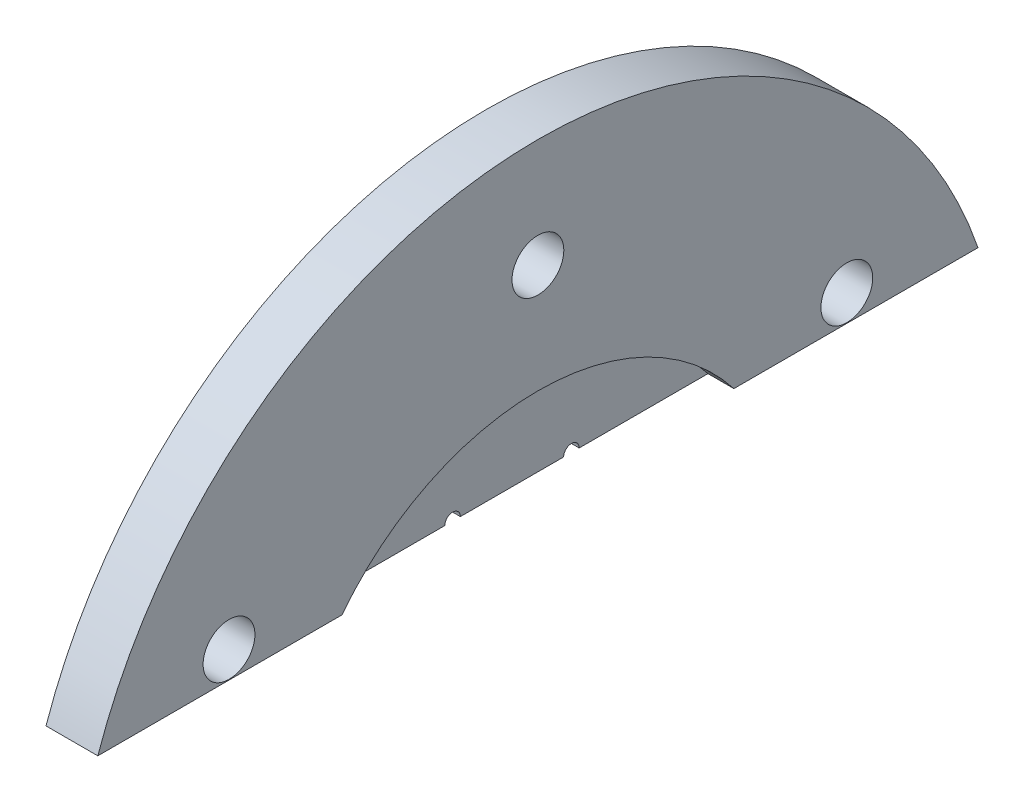
SolidWorks part; units mm, degrees
ref_plane "Front Plane" through (0, 0, 0) normal (0, 0, 1) x (1, 0, 0)
ref_plane "Top Plane" through (0, 0, 0) normal (0, 1, 0) x (1, 0, 0)
ref_plane "Right Plane" through (0, 0, 0) normal (1, 0, 0) x (0, 0, -1)
sketch "Sketch1" plane through (0, 0, 0) normal (1, 0, 0) x (0, 0, -1)
  circle A0 centre (0, 0) radius 89.825
  circle A1 centre (0, 0) radius 47.825
  dimension "D1" = 179.65
  dimension "D2" = 95.65
extrude "Boss-Extrude1" add sketch "Sketch1" along normal blind 10
sketch "Sketch3" plane through (0, 0, 0) normal (-1, 0, 0) x (0, 0, 1)
  circle A0 centre (0, 0) radius 47.825
  dimension "D1" = 95.65
extrude "tbh idk" add sketch "Sketch3" against normal blind 5
sketch "Sketch4" plane through (0, 0, 0) normal (-1, 0, 0) x (0, 0, 1)
  circle A0 centre (0, 0) radius 47.825
  dimension "D1" = 95.65
extrude "Extrusion to Fuel Man" add sketch "Sketch4" along normal blind 5
sketch "Ox Profile" plane through (-5, 0, 0) normal (-1, 0, 0) x (0, 0, 1)
  line L0 (0, 23.8051) -> (0, 34.7601) construction
  line L1 (0, -8.25) -> (0, 8.25) construction
  circle A0 centre (0, 29.2826) radius 1.25 construction
  circle A1 centre (11.4641, 29.2826) radius 1.5
  circle A2 centre (-11.4641, 29.2826) radius 1.5
  point P11 (0, 29.2826)
  dimension "D1" = 2.5
  dimension "D3" = 3
  dimension "D2" = 29.2826
  dimension "D4" = 11.4641
extrude "Ox Downcomer" cut sketch "Ox Profile" against normal up to next
pattern_circular "Ox Orifices" count 3 over 360 about axis through (0, -0.0577, 0) along (1, 0, 0) of "Ox Downcomer"
sketch "Sketch7" plane through (-5, 0, 0) normal (-1, 0, 0) x (0, 0, 1)
  line L0 (-6.9641, 29.2826) -> (6.9641, 29.2826) construction
  line L1 (-31.0915, -4.7131) -> (-11.4641, 29.2826) construction
  line L2 (-34.9886, -2.4631) -> (-15.3612, 31.5326)
  line L3 (31.0915, -4.7131) -> (11.4641, 29.2826) construction
  line L4 (15.3612, 31.5326) -> (34.9886, -2.4631)
  line L5 (-19.6274, -24.5695) -> (19.6274, -24.5695) construction
  line L6 (-19.6274, -29.0695) -> (19.6274, -29.0695)
  circle A0 centre (-11.4641, 29.2826) radius 4.5 construction
  circle A1 centre (11.4641, 29.2826) radius 4.5 construction
  arc A2 (-6.9641, 29.2826) -> (6.9641, 29.2826) centre (0, 29.2826) ccw
  circle A3 centre (31.0915, -4.7131) radius 4.5 construction
  arc A4 (28.8415, -8.6102) -> (21.8774, -20.6724) centre (25.3595, -14.6413) ccw
  circle A5 centre (19.6274, -24.5695) radius 4.5 construction
  circle A6 centre (-19.6274, -24.5695) radius 4.5 construction
  arc A7 (-21.8774, -20.6724) -> (-28.8415, -8.6102) centre (-25.3595, -14.6413) ccw
  circle A8 centre (-31.0915, -4.7131) radius 4.5 construction
  arc A9 (-15.3612, 31.5326) -> (-6.9641, 29.2826) centre (-11.4641, 29.2826) cw
  arc A10 (-34.9886, -2.4631) -> (-28.8415, -8.6102) centre (-31.0915, -4.7131) ccw
  arc A11 (6.9641, 29.2826) -> (15.3612, 31.5326) centre (11.4641, 29.2826) cw
  arc A12 (28.8415, -8.6102) -> (34.9886, -2.4631) centre (31.0915, -4.7131) ccw
  arc A13 (21.8774, -20.6724) -> (19.6274, -29.0695) centre (19.6274, -24.5695) cw
  arc A14 (-21.8774, -20.6724) -> (-19.6274, -29.0695) centre (-19.6274, -24.5695) ccw
  circle A15 centre (0, 0) radius 47.825
  point P25 (0, 0)
  dimension "D2" = 4.5
  dimension "D3" = 95.65
  dimension "D1" = 3
extrude "Fuel Blockers" cut sketch "Sketch7" against normal blind 5
sketch "Sketch8" plane through (5, 0, 0) normal (1, 0, 0) x (0, 0, -1)
  circle A0 centre (0, 0) radius 25.085
  dimension "D1" = 50.17
extrude "TI Cut Extrude" cut sketch "Sketch8" against normal through all
sketch "Sketch9" plane through (0, 0, 0) normal (-1, 0, 0) x (0, 0, 1)
  line L0 (-15.3612, 31.5326) -> (-34.9886, -2.4631) construction
  line L1 (-15.3612, 31.5326) -> (-34.9886, -2.4631)
  line L3 (34.9886, -2.4631) -> (15.3612, 31.5326)
  line L4 (-19.6274, -29.0695) -> (19.6274, -29.0695)
  line L5 (-15.3612, 31.5326) -> (-34.9886, -2.4631)
  line L6 (34.9886, -2.4631) -> (15.3612, 31.5326)
  line L7 (-19.6274, -29.0695) -> (19.6274, -29.0695)
  line L8 (-15.3612, 31.5326) -> (-34.9886, -2.4631)
  circle A0 centre (0, 0) radius 51.325
  arc A1 (15.3612, 31.5326) -> (6.9641, 29.2826) centre (11.4641, 29.2826) ccw construction
  arc A2 (-34.9886, -2.4631) -> (-28.8415, -8.6102) centre (-31.0915, -4.7131) ccw construction
  arc A3 (15.3612, 31.5326) -> (6.9641, 29.2826) centre (11.4641, 29.2826) ccw
  arc A4 (-34.9886, -2.4631) -> (-28.8415, -8.6102) centre (-31.0915, -4.7131) ccw
  arc A5 (-18.7096, -16.7095) -> (18.7096, -16.7095) centre (0, 0) ccw construction
  arc A6 (23.8257, -7.8482) -> (5.1161, 24.5577) centre (0, 0) ccw construction
  arc A7 (-5.1161, 24.5577) -> (-23.8257, -7.8482) centre (0, 0) ccw construction
  arc A8 (-18.7096, -16.7095) -> (18.7096, -16.7095) centre (0, 0) ccw
  arc A9 (23.8257, -7.8482) -> (5.1161, 24.5577) centre (0, 0) ccw
  arc A10 (-5.1161, 24.5577) -> (-23.8257, -7.8482) centre (0, 0) ccw
  arc A16 (-6.9641, 29.2826) -> (-5.1161, 24.5577) centre (0, 29.2826) ccw
  arc A17 (5.1161, 24.5577) -> (-5.1161, 24.5577) centre (0, 0) ccw
  arc A18 (5.1161, 24.5577) -> (6.9641, 29.2826) centre (0, 29.2826) ccw
  arc A19 (15.3612, 31.5326) -> (6.9641, 29.2826) centre (11.4641, 29.2826) ccw
  arc A20 (28.8415, -8.6102) -> (34.9886, -2.4631) centre (31.0915, -4.7131) ccw
  arc A21 (28.8415, -8.6102) -> (23.8257, -7.8482) centre (25.3595, -14.6413) ccw
  arc A22 (18.7096, -16.7095) -> (23.8257, -7.8482) centre (0, 0) ccw
  arc A23 (18.7096, -16.7095) -> (21.8774, -20.6724) centre (25.3595, -14.6413) ccw
  arc A24 (19.6274, -29.0695) -> (21.8774, -20.6724) centre (19.6274, -24.5695) ccw
  arc A25 (-21.8774, -20.6724) -> (-19.6274, -29.0695) centre (-19.6274, -24.5695) ccw
  arc A26 (-21.8774, -20.6724) -> (-18.7096, -16.7095) centre (-25.3595, -14.6413) ccw
  arc A27 (-23.8257, -7.8482) -> (-18.7096, -16.7095) centre (0, 0) ccw
  arc A28 (-23.8257, -7.8482) -> (-28.8415, -8.6102) centre (-25.3595, -14.6413) ccw
  arc A29 (-34.9886, -2.4631) -> (-28.8415, -8.6102) centre (-31.0915, -4.7131) ccw
  arc A30 (-6.9641, 29.2826) -> (-15.3612, 31.5326) centre (-11.4641, 29.2826) ccw
  arc A31 (-6.9641, 29.2826) -> (-5.1161, 24.5577) centre (0, 29.2826) ccw
  arc A32 (5.1161, 24.5577) -> (-5.1161, 24.5577) centre (0, 0) ccw
  arc A33 (5.1161, 24.5577) -> (6.9641, 29.2826) centre (0, 29.2826) ccw
  arc A34 (15.3612, 31.5326) -> (6.9641, 29.2826) centre (11.4641, 29.2826) ccw
  arc A35 (28.8415, -8.6102) -> (34.9886, -2.4631) centre (31.0915, -4.7131) ccw
  arc A36 (28.8415, -8.6102) -> (23.8257, -7.8482) centre (25.3595, -14.6413) ccw
  arc A37 (18.7096, -16.7095) -> (23.8257, -7.8482) centre (0, 0) ccw
  arc A38 (18.7096, -16.7095) -> (21.8774, -20.6724) centre (25.3595, -14.6413) ccw
  arc A39 (19.6274, -29.0695) -> (21.8774, -20.6724) centre (19.6274, -24.5695) ccw
  arc A40 (-21.8774, -20.6724) -> (-19.6274, -29.0695) centre (-19.6274, -24.5695) ccw
  arc A41 (-21.8774, -20.6724) -> (-18.7096, -16.7095) centre (-25.3595, -14.6413) ccw
  arc A42 (-23.8257, -7.8482) -> (-18.7096, -16.7095) centre (0, 0) ccw
  arc A43 (-23.8257, -7.8482) -> (-28.8415, -8.6102) centre (-25.3595, -14.6413) ccw
  arc A44 (-34.9886, -2.4631) -> (-28.8415, -8.6102) centre (-31.0915, -4.7131) ccw
  arc A45 (-6.9641, 29.2826) -> (-15.3612, 31.5326) centre (-11.4641, 29.2826) ccw
  arc M3 (-6.9641, 29.2826) -> (-5.1161, 24.5577) centre (0, 29.2826) ccw
  arc M4 (-5.1161, 24.5577) -> (5.1161, 24.5577) centre (0, 0) cw
  arc M5 (5.1161, 24.5577) -> (6.9641, 29.2826) centre (0, 29.2826) ccw
  arc M6 (6.9641, 29.2826) -> (15.3612, 31.5326) centre (11.4641, 29.2826) cw
  line M7 (15.3612, 31.5326) -> (34.9886, -2.4631)
  arc M8 (34.9886, -2.4631) -> (28.8415, -8.6102) centre (31.0915, -4.7131) cw
  arc M9 (28.8415, -8.6102) -> (23.8257, -7.8482) centre (25.3595, -14.6413) ccw
  arc M10 (23.8257, -7.8482) -> (18.7096, -16.7095) centre (0, 0) cw
  arc M11 (18.7096, -16.7095) -> (21.8774, -20.6724) centre (25.3595, -14.6413) ccw
  arc M12 (21.8774, -20.6724) -> (19.6274, -29.0695) centre (19.6274, -24.5695) cw
  line M13 (19.6274, -29.0695) -> (-19.6274, -29.0695)
  arc M14 (-19.6274, -29.0695) -> (-21.8774, -20.6724) centre (-19.6274, -24.5695) cw
  arc M15 (-21.8774, -20.6724) -> (-18.7096, -16.7095) centre (-25.3595, -14.6413) ccw
  arc M16 (-18.7096, -16.7095) -> (-23.8257, -7.8482) centre (0, 0) cw
  arc M17 (-23.8257, -7.8482) -> (-28.8415, -8.6102) centre (-25.3595, -14.6413) ccw
  arc M18 (-28.8415, -8.6102) -> (-34.9886, -2.4631) centre (-31.0915, -4.7131) cw
  line M19 (-34.9886, -2.4631) -> (-15.3612, 31.5326)
  arc M20 (-15.3612, 31.5326) -> (-6.9641, 29.2826) centre (-11.4641, 29.2826) cw
  dimension "D1" = 102.65
extrude "Fuel Volume" cut sketch "Sketch9" against normal blind 2 contours A0 M20 M3 M4 M5 M6 M7 M8 M9 M10 M11 M12 M13 M14 M15 M16 M17 M18 M19
sketch "Sketch10" plane through (10, 0, 0) normal (1, 0, 0) x (0, 0, -1)
  line L0 (0, 47.825) -> (0, 89.825) construction
  circle A0 centre (0, 68.825) radius 5
  circle A2 centre (0, 0) radius 89.825 construction
  circle A3 centre (0, 0) radius 47.825 construction
  circle A4 centre (0, 0) radius 47.825 construction
  circle A5 centre (0, 0) radius 89.825 construction
  circle A6 centre (59.6042, 34.4125) radius 5
  circle A7 centre (59.6042, -34.4125) radius 5
  circle A8 centre (0, -68.825) radius 5
  circle A9 centre (-59.6042, -34.4125) radius 5
  circle A10 centre (-59.6042, 34.4125) radius 5
  point P25 (0, 0)
  dimension "D1" = 10
  dimension "D2" = 6
extrude "Cut-Extrude1" cut sketch "Sketch10" against normal through all
sketch "Sketch11" plane through (5, 0, 0) normal (1, 0, 0) x (0, 0, -1)
  circle A8 centre (-11.4641, 29.2826) radius 4.2201
  circle A9 centre (11.4641, 29.2826) radius 3.8602
  point P4 (-11.4641, 29.2826)
  point P5 (11.4641, 29.2826)
ref_plane "Plane1" through (0, 29.2826, 0) normal (0, 1, 0) x (1, 0, 0)
sketch "Sketch12" plane through (0, 29.2826, 0) normal (0, 1, 0) x (1, 0, 0)
  line L0 (-5, -35.5915) -> (2, -35.5915) construction
  line L1 (-5, -28.8415) -> (-5, -35.5915) construction
  line L2 (2, 35.5915) -> (-5, 35.5915) construction
  line L3 (-5, 35.5915) -> (-5, 28.8415) construction
  line L4 (-5, 15.3612) -> (-5, 34.9886) construction
  line L5 (-5, 18.7096) -> (-5, -18.7096) construction
  line L6 (-5, -6.9641) -> (-5, -15.3612) construction
  line L7 (-5, -34.9886) -> (-5, -15.3612) construction
  line L9 (0, 89.825) -> (0, -89.825) construction
  line L10 (0, -89.825) -> (10, -89.825) construction
  line L11 (10, -89.825) -> (10, 89.825) construction
  line L12 (10, 89.825) -> (0, 89.825) construction
  line L13 (-5, -35.5915) -> (0, -35.5915)
  line L14 (-5, -28.8415) -> (-5, -35.5915)
  line L15 (0, 35.5915) -> (-5, 35.5915)
  line L16 (-5, 35.5915) -> (-5, 28.8415)
  line L17 (-5, 15.3612) -> (-5, 34.9886)
  line L18 (-5, 18.7096) -> (-5, -18.7096)
  line L19 (-5, -6.9641) -> (-5, -15.3612)
  line L20 (-5, -34.9886) -> (-5, -15.3612)
  line L22 (0, 89.825) -> (0, -89.825)
  line L23 (0, -89.825) -> (10, -89.825)
  line L24 (10, -89.825) -> (10, 89.825)
  line L25 (10, 89.825) -> (0, 89.825)
  point P13 (0, 35.5915)
  point P19 (0, -35.5915)
extrude "Cut-Extrude2" cut sketch "Sketch12" against normal through all contours L24 L25 L22 L23 | L22 L15 L16 L17 L18 L20 L14 L13
equation "\"Flange_Dia\"= 179.65"
equation "\"Regen_Thickness\"= 1.5"
equation "\"Regen_To_Inner\"=2"
equation "\"Faceplate_Area\"=95.65"
equation "\"Regen_Rib_Thickness\"=1"
equation "\"Flange_Thickness\"= 10"
equation "\"Faceplate_To_Chamber_Extrusion\"=1"
equation "\"Injector_MCCN_O-Ring\"=3"
equation "\"Ox_Orifice\"= 3"
equation "\"Fuel_Orifice\"= 2.5"
equation "\"OxFuel_Dist_Downstream\"= 8"
equation "\"Fuel_Dist_From_Center\"=29.2826"
equation "\"OxFuel_HalfAngle\"=30"
equation "\"D1@Sketch1\"=\"Flange_Dia\""
equation "\"D2@Sketch1\"=\"Faceplate_Area\""
equation "\"D1@Boss-Extrude1\"=\"Flange_Thickness\""
equation "\"D1@Sketch3\"=\"Faceplate_Area\""
equation "\"D1@tbh idk\" = \"Flange_Thickness\" / 2"
equation "\"D1@Sketch4\"=\"Faceplate_Area\""
equation "\"D1@Extrusion to Fuel Man\" = \"Flange_Thickness\" / 2"
equation "\"D1@Ox Profile\" = \"Fuel_Orifice\""
equation "\"D2@Ox Profile\" = \"Fuel_Dist_From_Center\""
equation "\"D3@Ox Profile\" = \"Ox_Orifice\""
equation "\"D1@Flange\" = \"Flange_Thickness\""
equation "\"D1@Regen Slots Sketch\" = \"Regen_Rib_Thickness\""
equation "\"D2@Regen Slots Sketch\" = \"Regen_Thickness\""
equation "\"D3@Regen Slots Sketch\" = \"Regen_To_Inner\""
equation "\"D1@Faceplate Extrusion to Manifold Sketch\" = \"Faceplate_Area\""
equation "\"D1@Faceplate Extrusion to Chamber Sketch\" = \"Faceplate_Area\""
equation "\"D1@Faceplate Extrusion to Chamber\"=\"Faceplate_To_Chamber_Extrusion\""
equation "\"D1@O-Ring Slot Sketch\" = \"Faceplate_Area\""
equation "\"D2@O-Ring Slot Sketch\" = \"Injector_MCCN_O-Ring\""
equation "\"D1@O-Ring Slot\" =  ( \"Faceplate_To_Chamber_Extrusion\" )  +  ( \"Injector_MCCN_O-Ring\" / 2 ) "
equation "\"D1@Fuel Orifices Sketch\" = \"Ox_Orifice\""
equation "\"D2@Fuel Orifices Sketch\" = \"Fuel_Orifice\""
equation "\"D5@Fuel Orifices Sketch\" = \"Fuel_Dist_From_Center\""
equation "\"D3@Fuel Orifices Sketch\" = \"OxFuel_Dist_Downstream\""
equation "\"D4@Fuel Orifices Sketch\" = \"OxFuel_Dist_Downstream\""
equation "\"D1@Ox1 Profile\" = \"Ox_Orifice\""
equation "\"D1@Ox2 Profile\" = \"Ox_Orifice\""
equation "\"D1@Ox2 Guide Curve\" = \"OxFuel_HalfAngle\""
equation "\"D2@Ox1 Profile\" = \"OxFuel_Dist_Downstream\""
equation "\"D2@Ox2 Profile\"=\"OxFuel_Dist_Downstream\""
equation "\"D1@Ox1 Guide Curve\"=\"OxFuel_HalfAngle\""
equation "\"Thickness_FuelMan\"=5"
equation "\"D1@Faceplate Extrusion to Manifold\"=\"Thickness_FuelMan\""
equation "\"OxFuel_Dist_Upstream\"=(((\"Thickness_FuelMan\" + \"Faceplate_To_Chamber_Extrusion\")*tan(\"OxFuel_HalfAngle\")))+(\"OxFuel_Dist_Downstream\")"
equation "\"D4@Ox Profile\"=\"OxFuel_Dist_Upstream\""
equation "\"D7@Fuel Orifices Sketch\"=2*\"Fuel_Dist_From_Center\""
equation "\"D2@Sketch7\"=\"Ox_Orifice\"*1.5"
equation "\"D3@Sketch7\"=\"Faceplate_Area\""
equation "\"D1@Fuel Blockers\" = \"Thickness_FuelMan\""
equation "\"Torch_Igniter_OD\"=50.17"
equation "\"D1@Sketch8\"=\"Torch_Igniter_OD\""
equation "\"D1@Sketch9\"=\"Faceplate_Area\"+2*(\"Regen_To_Inner\"+\"Regen_Thickness\")"
equation "\"Fuel_Recess_In_OxMan\"=2"
equation "\"D1@Fuel Volume\" = \"Fuel_Recess_In_OxMan\""
